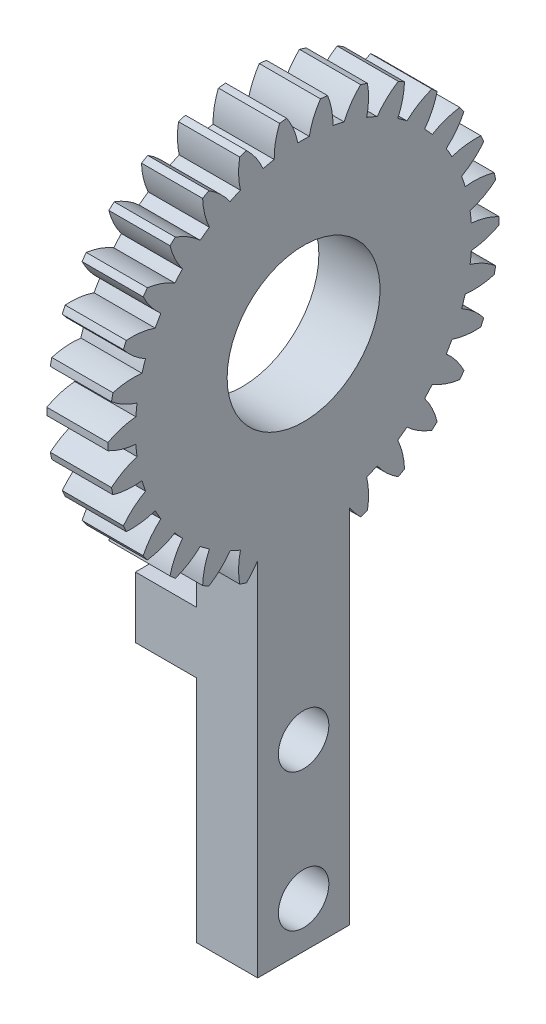
SolidWorks part; units mm, degrees
ref_plane "Plane1" through (0, 0, 0) normal (0, 0, 1) x (1, 0, 0)
ref_plane "Plane2" through (0, 0, 0) normal (0, 1, 0) x (1, 0, 0)
ref_plane "Plane3" through (0, 0, 0) normal (1, 0, 0) x (0, 0, -1)
other "Configuration Table"
sketch "HoldingSke" plane through (0, 0, 0) normal (0, 1, 0) x (1, 0, 0)
  line L0 (0, 0) -> (1.0825, -0.625)
  line L1 (-15, 0) -> (100, 0) construction
  line L2 (0, 0) -> (-2.1039, 2.3779)
  line L3 (0, 0) -> (-11.863, 4.5341)
  line L4 (0, 0) -> (7.479, 4.318)
  line L5 (0, 0) -> (-46.8476, -17.4728)
  line L6 (0, 0) -> (-3.3159, -2.2372)
  line L7 (-2.1039, 2.3779) -> (8.6586, 51.2059)
  line L8 (-76.2, 54.61) -> (-74.4, 54.61)
  line L9 (-71.009, 38.7566) -> (-53.1078, 45.2721)
  line L10 (-76.2, 71.12) -> (104.1128, 71.12)
  line L11 (0, 0) -> (-4, 0)
  line L12 (-76.2, 101.6) -> (-76.17, 101.6)
  line L13 (24.9733, 27.94) -> (52.9518, 28.4284)
  line L14 (24.9733, 27.94) -> (24.9743, 27.94)
  line L15 (24.9733, 27.94) -> (100.4006, 29.5858)
  line L16 (-63.627, -0.8) -> (-12.827, -0.8)
  circle A0 centre (0, 0) radius 5
  circle A1 centre (0, 0) radius 10.999
  circle A2 centre (0, 0) radius 37.5
  circle A3 centre (0, 0) radius 5
  dimension "MHD" = 21.998
  dimension "Hub_dia" = 75
  dimension "Bore" = 10
  dimension "MBD" = 10
  dimension "Num_teeth" = 30
  dimension "Pitch" = 1.25
  dimension "Overall_len" = 50
  dimension "Show_teeth" = 30
  dimension "Thickness" = 4
  dimension "OAL" = 50.0001
  dimension "T_dim" = 1.8
  dimension "Ap" = 20
  dimension "H" = 19.05
  dimension "Pitch_radius" = 180.3128
  dimension "Width" = 4
  dimension "Backlash" = 0.03
  dimension "Addendum_fac" = 1
  dimension "Dedendum_fac" = 1.25
  dimension "Clearance_fac" = 0.25
  dimension "Dedendum_add" = 0.001
  dimension "Module" = 0.8
sketch "BasProSke" plane through (0, 0, 0) normal (0, 1, 0) x (1, 0, 0)
  line L0 (-10, 0) -> (60, 0) construction
  line L1 (0, 0) -> (0, 12.8)
  line L2 (0, 0) -> (4, 0)
  line L3 (4, 0) -> (4, 12.8)
  line L4 (4, 12.8) -> (0, 12.8)
  dimension "Thickness" = 4
  dimension "Diameter" = 25.6
revolve "Base-Revolve" add sketch "BasProSke" angle 360 about L0
sketch "TooCutSke" plane through (0, 0, 0) normal (1, 0, 0) x (0, 0, -1)
  line L1 (0, 0) -> (0, 107) construction
  line L2 (0, 0) -> (-0.6805, 11.9807) construction
  line L3 (0, 0) -> (-2.5058, 23.8411) construction
  line L4 (-0.6805, 11.9807) -> (-1.2529, 11.9205) construction
  arc A0 (0.3724, 10.9927) -> (-0.3724, 10.9927) centre (0, 0) ccw
  arc A1 (1.1205, 12.7764) -> (-1.1205, 12.7764) centre (0, 0) ccw
  circle A2 centre (0, 0) radius 12 construction
  circle A3 centre (0, 0) radius 11.2763 construction
  arc A4 (-0.3724, 10.9927) -> (-1.1205, 12.7764) centre (-5.0822, 10.0661) ccw
  arc A5 (1.1205, 12.7764) -> (0.3724, 10.9927) centre (5.0822, 10.0661) ccw
  dimension "Root_dia" = 21.998
  dimension "Overcut_dia" = 25.6508
  dimension "Pitch_dia" = 24
  dimension "Base_dia" = 22.5526
  dimension "Flank_rad" = 4.8
  dimension "Half_ang" = 6
  dimension "Half_CT" = 0.5755
extrude "ToothCut" cut sketch "TooCutSke" along normal through all
fillet "Breaks" [suppressed] radius 0.016
fillet "RootFillets" [suppressed] radius 0.201
pattern_circular "TeethCuts" count 30 every 12 about axis through (-10, 0, 0) along (1, 0, 0) of "ToothCut", "RootFillets", "Breaks"
sketch "HubNeaOneSke" plane through (0, 0, 0) normal (-1, 0, 0) x (0, 0, 1)
  circle A0 centre (0, 0) radius 10.999
  dimension "Diameter" = 21.998
extrude "HubNearOne" [suppressed] add sketch "HubNeaOneSke" along normal blind 46.0001
sketch "HubNeaBotSke" plane through (0, 0, 0) normal (-1, 0, 0) x (0, 0, 1)
  circle A0 centre (0, 0) radius 10.999
  dimension "Diameter" = 21.998
extrude "HubNearBoth" [suppressed] add sketch "HubNeaBotSke" along normal blind 23
ref_plane "FarPln" through (4, 0, 0) normal (1, 0, 0) x (0, 0, -1)
sketch "HubFarSke" plane through (4, 0, 0) normal (1, 0, 0) x (0, 0, -1)
  circle A0 centre (0, 0) radius 10.999
  dimension "Diameter" = 21.998
extrude "HubFar" [suppressed] add sketch "HubFarSke" along normal blind 23
sketch "BorSke" plane through (0, 0, 0) normal (1, 0, 0) x (0, 0, -1)
  circle A0 centre (0, 0) radius 5
  dimension "Diameter" = 10
extrude "Bore" cut sketch "BorSke" along normal mid plane 100.0001
sketch "KeySke" plane through (0, 0, 0) normal (1, 0, 0) x (0, 0, -1)
  line L0 (-2, 0) -> (-2, 6.8)
  line L1 (-2, 6.8) -> (2, 6.8)
  line L2 (2, 6.8) -> (2, 0)
  line L3 (0, 0) -> (0, 34) construction
  line L4 (-2, 0) -> (2, 0)
  dimension "Width" = 4
  dimension "Offset" = 6.8
extrude "Keyway" [suppressed] cut sketch "KeySke" along normal mid plane 100.0001
pattern_circular "Keyway2" [suppressed] count 2 every 90 about axis through (-10, 0, 0) along (1, 0, 0)
sketch "草图1" plane through (4, 0, 0) normal (1, 0, 0) x (0, 0, -1)
  line L0 (0, 1.8258) -> (0, 0) construction
  line L1 (-3, -6.6367) -> (3, -6.6367)
  line L2 (-3, -6.6367) -> (-3, -35)
  line L3 (-3, -35) -> (3, -35)
  line L4 (3, -6.6367) -> (3, -35)
  point P7 (0, -6.6367)
  dimension "D1" = 35
  dimension "D2" = 6
extrude "凸台-拉伸1" add sketch "草图1" against normal blind 4
sketch "草图4" plane through (0, 0, -3) normal (0, 0, -1) x (-1, 0, 0)
  line L1 (0, -35) -> (-2, -35)
  line L2 (0, -35) -> (0, -20)
  line L3 (0, -20) -> (-2, -20)
  line L4 (-2, -35) -> (-2, -20)
  dimension "D1" = 2
  dimension "D2" = 15
extrude "切除-拉伸2" cut sketch "草图4" against normal blind 6
sketch "草图6" plane through (2, 0, 0) normal (-1, 0, 0) x (0, 0, 1)
  line L0 (3, -20) -> (-3, -20) construction
  line L1 (3, -35) -> (-3, -35) construction
  circle A0 centre (0, -23) radius 1.65
  circle A1 centre (0, -32) radius 1.65
  dimension "D1" = 3
  dimension "D3" = 3.3
  dimension "D2" = 3
extrude "切除-拉伸3" cut sketch "草图6" against normal blind 4
sketch "草图7" plane through (4, 0, 0) normal (1, 0, 0) x (0, 0, -1)
  circle A0 centre (0, 0) radius 12
  dimension "D1" = 24
sketch "草图8" plane through (2, 0, 0) normal (-1, 0, 0) x (0, 0, 1)
  line L1 (-3, -20) -> (3, -20)
  line L2 (-3, -20) -> (-3, -35)
  line L3 (-3, -35) -> (3, -35)
  line L4 (3, -20) -> (3, -35)
  circle A0 centre (0, -23) radius 1.65
  circle A1 centre (0, -32) radius 1.65
extrude "凸台-拉伸2" add sketch "草图8" along normal blind 2
sketch "草图9" plane through (0, 0, 3) normal (0, 0, 1) x (1, 0, 0)
  line L0 (0, -11.3438) -> (0, -35) construction
  line L1 (0, -20) -> (-4, -20)
  line L2 (0, -20) -> (0, -16)
  line L3 (0, -16) -> (-4, -16)
  line L4 (-4, -20) -> (-4, -16)
  line L5 (0, -20) -> (-4, -20) construction
  dimension "D1" = 4
extrude "凸台-拉伸3" add sketch "草图9" against normal blind 6
equation "' \"Module@HoldingSke\" = 6.35"
equation "' \"Num_teeth@HoldingSke\" = 12"
equation "' \"Ap@HoldingSke\" =  20"
equation "' \"Ap@HoldingSke\" = 20"
equation "' \"Width@HoldingSke\" = 0.5 * 25.4"
equation "' \"Hub_dia@HoldingSke\"= 1 * 25.4"
equation "' \"Hub_dia@HoldingSke\" = 1 * 25.4"
equation "' \"Overall_len@HoldingSke\" = 1.0 * 25.4"
equation "' \"Bore@HoldingSke\" = 0.75 * 25.4"
equation "' \"T_dim@HoldingSke\" = 0.1 * 25.4"
equation "' \"Width@KeySke\" = 0.25 * 25.4"
equation "' \"Show_teeth@HoldingSke\" = 13"
equation "' \"Backlash@HoldingSke\" = 0.009 * 25.4"
equation "' \"Addendum_fac@HoldingSke\" = 1.0"
equation "' \"Dedendum_fac@HoldingSke\" = 1.25"
equation "' \"Dedendum_add@HoldingSke\" = 0.00005 * 25.4"
equation "' \"Clearance_fac@HoldingSke\" = 0.25"
equation "\"Pitch@HoldingSke\" = 1 / \"Module@HoldingSke\""
equation "\"Overcut_dia@TooCutSke\" = (\"Num_teeth@HoldingSke\" + 2 * \"Addendum_fac@HoldingSke\") / \"Pitch@HoldingSke\" + 0.002 * 25.4"
equation "\"Pitch_dia@TooCutSke\" = \"Num_teeth@HoldingSke\" / \"Pitch@HoldingSke\""
equation "\"Base_dia@TooCutSke\" = \"Num_teeth@HoldingSke\" / \"Pitch@HoldingSke\" * cos((\"Ap@HoldingSke\"  * 3.14159265 / 180))"
equation "\"Root_dia@TooCutSke\" = (\"Num_teeth@HoldingSke\" + 2) / \"Pitch@HoldingSke\" - 2 * (\"Addendum_fac@HoldingSke\" + \"Dedendum_fac@HoldingSke\") / \"Pitch@HoldingSke\" - \"Dedendum_add@HoldingSke\" * 2"
equation "\"Half_ang@TooCutSke\" = 180 / \"Num_teeth@HoldingSke\""
equation "\"Half_CT@TooCutSke\" = \"Num_teeth@HoldingSke\" / \"Pitch@HoldingSke\" * sin((3.14159265 / 2 / \"Num_teeth@HoldingSke\")) / 2 - 7 * \"Backlash@HoldingSke\" / 4"
equation "\"Flank_rad@TooCutSke\" = \"Num_teeth@HoldingSke\" / \"Pitch@HoldingSke\" / 5"
equation "\"Radius@RootFillets\" = \"Clearance_fac@HoldingSke\" / \"Pitch@HoldingSke\" + \"Dedendum_add@HoldingSke\""
equation "\"Break_rad@Breaks\" = 0.02 / \"Pitch@HoldingSke\""
equation "\"Thickness@HoldingSke\" = \"Width@HoldingSke\""
equation "\"OAL@HoldingSke\" = \"Thickness@HoldingSke\""
equation "\"MHD@HoldingSke\" = (\"Num_teeth@HoldingSke\" + 2) / \"Pitch@HoldingSke\" - 2 * (\"Addendum_fac@HoldingSke\" + \"Dedendum_fac@HoldingSke\")  / \"Pitch@HoldingSke\" - \"Dedendum_add@HoldingSke\" * 2"
equation "\"MBD@HoldingSke\" = (\"Num_teeth@HoldingSke\" + 2) / \"Pitch@HoldingSke\" - 2 * (\"Addendum_fac@HoldingSke\" + \"Dedendum_fac@HoldingSke\")  / \"Pitch@HoldingSke\" - \"Dedendum_add@HoldingSke\" * 2 - 0.002 * 25.4"
equation "\"MHD@HoldingSke\" = ((sgn( \"MHD@HoldingSke\" - \"Hub_dia@HoldingSke\" )-1)*( \"MHD@HoldingSke\" - \"Hub_dia@HoldingSke\" ))/-2+ \"Hub_dia@HoldingSke\""
equation "\"MBD@HoldingSke\" = ((sgn( \"MBD@HoldingSke\" - \"Bore@HoldingSke\" )-1)*( \"MBD@HoldingSke\" - \"Bore@HoldingSke\" ))/-2+ \"Bore@HoldingSke\""
equation "\"OAL@HoldingSke\" = ((sgn( \"OAL@HoldingSke\" - \"Overall_len@HoldingSke\" )+1)*( \"OAL@HoldingSke\" - \"Overall_len@HoldingSke\" ))/2 + \"Overall_len@HoldingSke\" + 0.000002 * 25.4"
equation "\"Num_teeth@TeethCuts\" = int( \"Show_teeth@HoldingSke\" ) + 1"
equation "\"Num_teeth@TeethCuts\" = ((sgn( \"Num_teeth@TeethCuts\" - \"Num_teeth@HoldingSke\" )-1)*( \"Num_teeth@TeethCuts\" - \"Num_teeth@HoldingSke\" ))/-2+ \"Num_teeth@HoldingSke\""
equation "\"Num_teeth@TeethCuts\" = ((sgn( \"Num_teeth@TeethCuts\" - 2.0)+1)*( \"Num_teeth@TeethCuts\" - 2.0))/2 +2.0"
equation "\"Angle@TeethCuts\" = 360.0 / \"Num_teeth@HoldingSke\""
equation "\"Diameter@BasProSke\" = (\"Num_teeth@HoldingSke\" + 2 * \"Addendum_fac@HoldingSke\") / \"Pitch@HoldingSke\""
equation "\"Thickness@BasProSke\"  = \"Thickness@HoldingSke\""
equation "' \"Fillet_rad@BasProSke\" =  \"Thickness@HoldingSke\" * 0.05"
equation "' \"Fillet_rad@BasProSke\" = \"Thickness@HoldingSke\" * 0.05"
equation "\"MHD@HoldingSke\" = ((sgn( \"MHD@HoldingSke\" - \"Root_dia@TooCutSke\" )-1)*( \"MHD@HoldingSke\" - \"Root_dia@TooCutSke\" ))/-2+ \"Root_dia@TooCutSke\""
equation "\"Diameter@HubNeaOneSke\" = \"MHD@HoldingSke\""
equation "\"Length@HubNearOne\" = \"OAL@HoldingSke\" - \"Thickness@BasProSke\""
equation "\"Diameter@HubNeaBotSke\" = \"MHD@HoldingSke\""
equation "\"Length@HubNearBoth\" = ( \"OAL@HoldingSke\" - \"Thickness@BasProSke\" ) / 2.0"
equation "\"Thickness@FarPln\" = \"Thickness@BasProSke\""
equation "\"Diameter@HubFarSke\" = \"MHD@HoldingSke\""
equation "\"Length@HubFar\" = ( \"OAL@HoldingSke\" - \"Thickness@BasProSke\" ) / 2.0"
equation "\"Diameter@BorSke\" = \"MBD@HoldingSke\""
equation "\"D1@Bore\" = \"OAL@HoldingSke\" * 2.0"
equation "\"D1@Keyway\" = \"OAL@HoldingSke\" * 2.0"
equation "\"Offset@KeySke\" = \"T_dim@HoldingSke\" + \"MBD@HoldingSke\" / 2.0"
